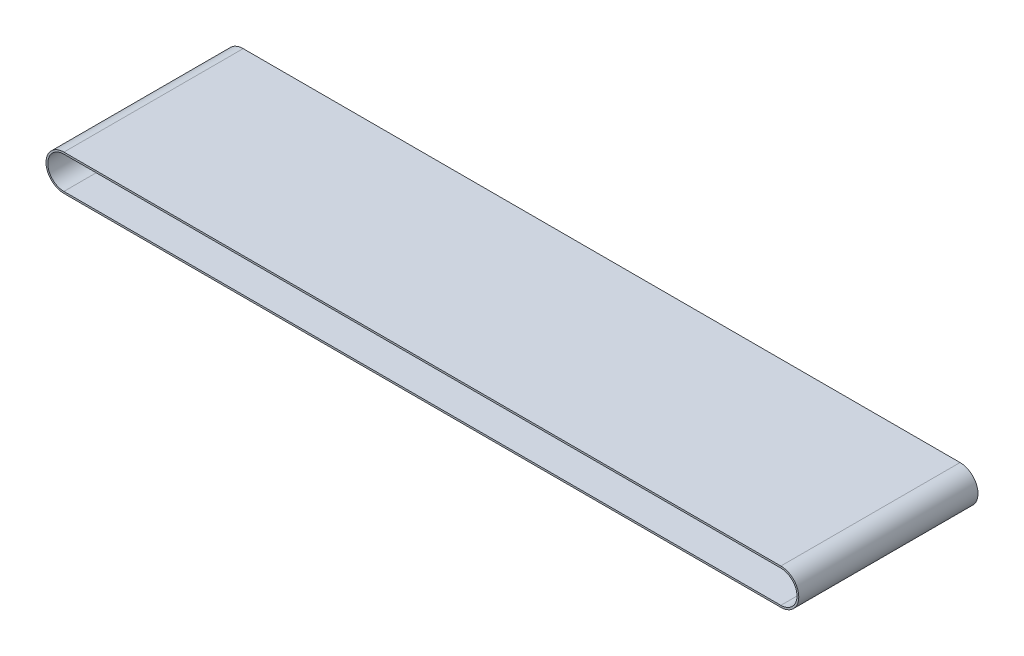
SolidWorks part; units mm, degrees
ref_plane "Front Plane" through (0, 0, 0) normal (0, 0, 1) x (1, 0, 0)
ref_plane "Top Plane" through (0, 0, 0) normal (0, 1, 0) x (1, 0, 0)
ref_plane "Right Plane" through (0, 0, 0) normal (1, 0, 0) x (0, 0, -1)
sketch "Sketch1" plane through (0, 0, 0) normal (0, 0, 1) x (1, 0, 0)
  line L0 (0, 0) -> (4000, 0) construction
  line L1 (0, 100) -> (4000, 100)
  line L2 (0, -100) -> (4000, -100)
  line L3 (0, 90) -> (4000, 90)
  line L4 (0, -90) -> (4000, -90)
  arc A0 (0, 100) -> (0, -100) centre (0, 0) ccw
  arc A1 (4000, -100) -> (4000, 100) centre (4000, 0) ccw
  arc A2 (4000, -90) -> (4000, 90) centre (4000, 0) ccw
  arc A3 (0, 90) -> (0, -90) centre (0, 0) ccw
  point P3 (2000, 0)
  dimension "D2" = 100
  dimension "D1" = 4000
  dimension "D3" = 10
extrude "Boss-Extrude1" add sketch "Sketch1" along normal blind 1000
